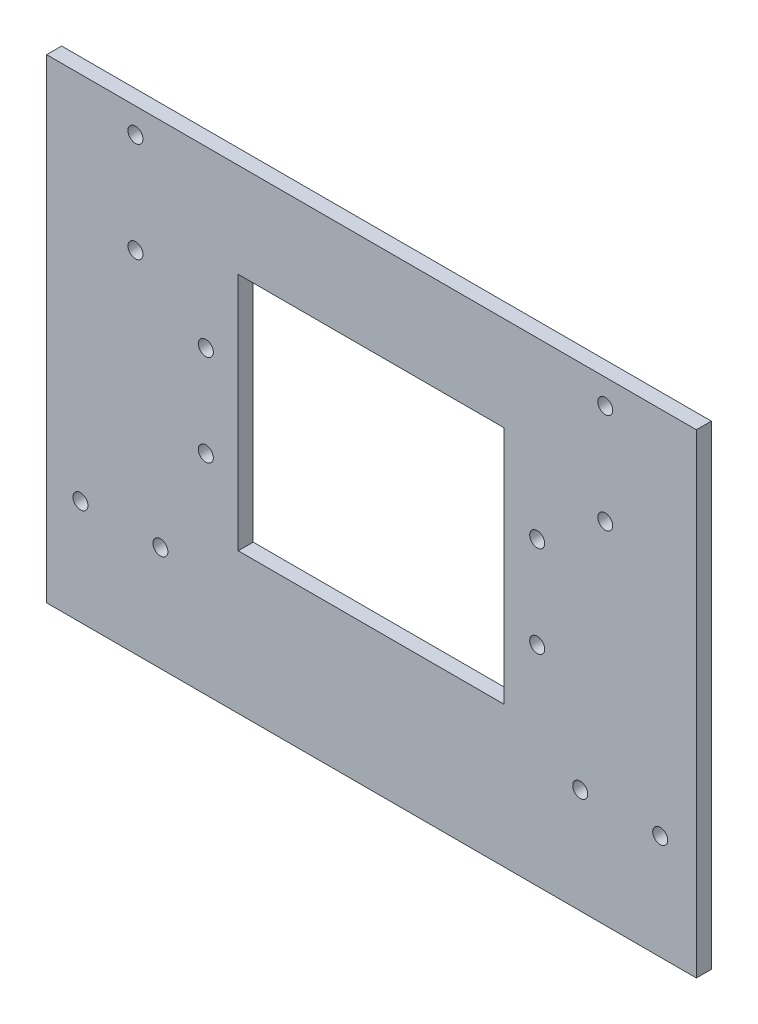
SolidWorks part; units mm, degrees
ref_plane "前视基准面" through (0, 0, 0) normal (0, 0, 1) x (1, 0, 0)
ref_plane "上视基准面" through (0, 0, 0) normal (0, 1, 0) x (1, 0, 0)
ref_plane "右视基准面" through (0, 0, 0) normal (1, 0, 0) x (0, 0, -1)
sketch "草图1" plane through (0, 0, 0) normal (0, 0, 1) x (1, 0, 0)
  line L1 (65, -47.5) -> (-65, -47.5)
  line L2 (65, -47.5) -> (65, 47.5)
  line L3 (65, 47.5) -> (-65, 47.5)
  line L4 (-65, -47.5) -> (-65, 47.5)
  line L5 (65, -47.5) -> (-65, 47.5) construction
  line L6 (65, 47.5) -> (-65, -47.5) construction
  point P0 (0, 0)
  dimension "D1" = 130
  dimension "D2" = 95
extrude "凸台-拉伸1" add sketch "草图1" along normal blind 3
sketch "草图2" plane through (0, 0, 3) normal (0, 0, 1) x (1, 0, 0)
  line L0 (0, -47.5) -> (0, -26.5) construction
  line L1 (-65, -47.5) -> (65, -47.5) construction
  line L2 (0, -26.5) -> (10, -26.5) construction
  circle A0 centre (10, -26.5) radius 1.5
  circle A1 centre (-10, -26.5) radius 1.5
  dimension "D3" = 3
  dimension "D1" = 21
  dimension "D2" = 10
sketch "草图3" plane through (0, 0, 0) normal (0, 0, -1) x (-1, 0, 0)
  circle A0 centre (-57.7671, -26.5) radius 1.5
  circle A1 centre (-41.7671, -26.5) radius 1.5
  circle A2 centre (42.2329, -26.5) radius 1.5
  circle A4 centre (58.2329, -26.5) radius 1.5
extrude "切除-拉伸2" cut sketch "草图3" against normal blind 10
sketch "草图4" plane through (0, 0, 0) normal (0, 0, -1) x (-1, 0, 0)
  circle A0 centre (-46.7671, 42.5) radius 1.5
  circle A1 centre (-46.7671, 22.5) radius 1.5
  circle A2 centre (47.2329, 42.5) radius 1.5
  circle A3 centre (47.2329, 22.5) radius 1.5
extrude "切除-拉伸3" cut sketch "草图4" against normal blind 10
sketch "草图15" plane through (0, 0, 0) normal (0, 0, -1) x (-1, 0, 0)
  circle A0 centre (0, 7.4526) radius 12.75
  dimension "D1" = 25.5
extrude "切除-拉伸8" cut sketch "草图15" against normal blind 10
sketch "草图16" plane through (0, 0, 0) normal (0, 0, -1) x (-1, 0, 0)
  line L1 (15.5, -8.0474) -> (-15.5, -8.0474) construction
  line L2 (15.5, -8.0474) -> (15.5, 22.9526) construction
  line L3 (15.5, 22.9526) -> (-15.5, 22.9526) construction
  line L4 (-15.5, -8.0474) -> (-15.5, 22.9526) construction
  line L5 (15.5, -8.0474) -> (-15.5, 22.9526) construction
  line L6 (15.5, 22.9526) -> (-15.5, -8.0474) construction
  circle A0 centre (-15.5, 22.9526) radius 1.25
  circle A1 centre (15.5, 22.9526) radius 1.25
  circle A2 centre (15.5, -8.0474) radius 1.25
  circle A3 centre (-15.5, -8.0474) radius 1.25
  point P0 (0, 7.4526)
  dimension "D3" = 2.5
  dimension "D4" = 2.5
  dimension "D5" = 2.5
  dimension "D6" = 2.5
  dimension "D1" = 31
  dimension "D2" = 31
extrude "切除-拉伸9" cut sketch "草图16" against normal blind 10
sketch "草图18" plane through (0, 0, 3) normal (0, 0, 1) x (1, 0, 0)
  line L1 (-26.6718, -19.3053) -> (26.4781, -19.3053)
  line L2 (-26.6718, -19.3053) -> (-26.6718, 28.6026)
  line L3 (-26.6718, 28.6026) -> (26.4781, 28.6026)
  line L4 (26.4781, -19.3053) -> (26.4781, 28.6026)
  circle A0 centre (-33.15, 12.6026) radius 1.5
  circle A1 centre (-33.15, -5.6974) radius 1.5
  circle A2 centre (33.15, 12.6026) radius 1.5
  circle A3 centre (33.15, -5.6974) radius 1.5
extrude "切除-拉伸10" cut sketch "草图18" against normal blind 10
